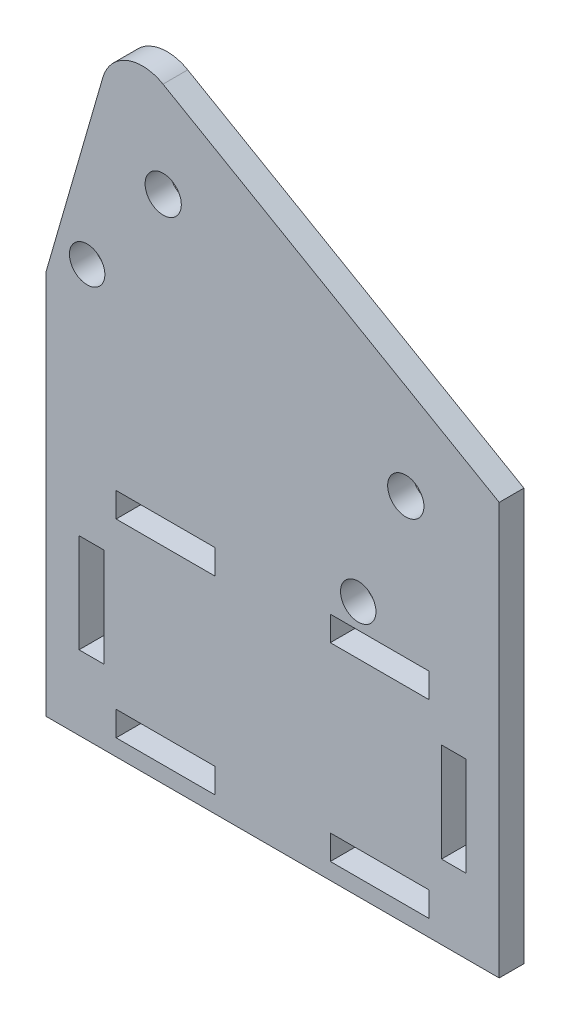
SolidWorks part; units mm, degrees
material "Thornel Mat VMA"
ref_plane "前视基准面" through (0, 0, 0) normal (0, 0, 1) x (1, 0, 0)
ref_plane "上视基准面" through (0, 0, 0) normal (0, 1, 0) x (1, 0, 0)
ref_plane "右视基准面" through (0, 0, 0) normal (1, 0, 0) x (0, 0, -1)
other "Configuration Table"
sketch "草图1" plane through (0, 0, 0) normal (0, 0, 1) x (1, 0, 0)
  line L0 (27.5, 15) -> (27.5, 35)
  line L1 (-27.5, 15) -> (27.5, 15)
  line L2 (-27.5, 15) -> (-27.5, -15)
  line L3 (-27.5, -15) -> (27.5, -15)
  line L4 (27.5, 15) -> (27.5, -15)
  line L5 (-27.5, 15) -> (27.5, -15) construction
  line L6 (-27.5, -15) -> (27.5, 15) construction
  line L7 (27.5, 35) -> (-27.5, 66.7543)
  line L8 (-27.5, 66.7543) -> (-27.5, 15)
  point P0 (0, 0)
  dimension "D1" = 30
  dimension "D2" = 55
  dimension "D3" = 20
  dimension "D4" = 60
extrude "凸台-拉伸1" add sketch "草图1" along normal blind 3 contours L7 L8 L1 L0 | L4 L1 L2 L3
sketch "草图2" plane through (0, 0, 3) normal (0, 0, 1) x (1, 0, 0)
  line L0 (0, 5.7338) -> (0, -5.8391) construction
  line L1 (-23.5, 13) -> (23.5, 13) construction
  line L2 (-23.5, 13) -> (-23.5, -13) construction
  line L3 (-23.5, -13) -> (23.5, -13) construction
  line L4 (23.5, 13) -> (23.5, -13) construction
  line L5 (-23.5, 13) -> (23.5, -13) construction
  line L6 (-23.5, -13) -> (23.5, 13) construction
  line L7 (-19, -13) -> (-7, -13)
  line L8 (-19, -13) -> (-19, -10)
  line L9 (-19, -10) -> (-7, -10)
  line L10 (-7, -13) -> (-7, -10)
  line L11 (19, -10) -> (7, -10)
  line L12 (7, -13) -> (7, -10)
  line L13 (19, -13) -> (7, -13)
  line L14 (19, -13) -> (19, -10)
  line L15 (-11.0901, 0) -> (13.8362, 0) construction
  line L16 (19, 13) -> (19, 10)
  line L17 (19, 13) -> (7, 13)
  line L18 (7, 13) -> (7, 10)
  line L19 (19, 10) -> (7, 10)
  line L20 (-19, 10) -> (-7, 10)
  line L21 (-7, 13) -> (-7, 10)
  line L22 (-19, 13) -> (-7, 13)
  line L23 (-19, 13) -> (-19, 10)
  line L24 (23.5, -6) -> (20.5, -6)
  line L25 (-23.5, 6) -> (-20.5, 6)
  line L26 (-23.5, 6) -> (-23.5, -6)
  line L27 (-23.5, -6) -> (-20.5, -6)
  line L28 (-20.5, 6) -> (-20.5, -6)
  line L29 (20.5, 6) -> (20.5, -6)
  line L30 (23.5, 6) -> (20.5, 6)
  line L31 (23.5, 6) -> (23.5, -6)
  point P0 (0, 0)
  point P30 (-20.5, 0)
  dimension "D1" = 47
  dimension "D2" = 26
  dimension "D3" = 3
  dimension "D4" = 12
  dimension "D5" = 7
  dimension "D6" = 3
  dimension "D7" = 12
extrude "切除-拉伸1" cut sketch "草图2" against normal blind 3
sketch "草图3" plane through (0, 0, 3) normal (0, 0, 1) x (1, 0, 0)
  line L0 (-13.2846, 47) -> (16.1603, 30) construction
  line L1 (27.5, 35) -> (-27.5, 66.7543) construction
  circle A0 centre (-13.2846, 47) radius 2.2
  circle A1 centre (16.1603, 30) radius 2.2
  dimension "D1" = 34
  dimension "D4" = 4.4
  dimension "D2" = 10
  dimension "D3" = 30
extrude "切除-拉伸2" cut sketch "草图3" against normal blind 10
sketch "草图4" plane through (0, 0, 3) normal (0, 0, 1) x (1, 0, 0)
  line L0 (-18.8397, 61.7543) -> (-27.5, 31.7543)
  line L1 (27.5, 35) -> (-27.5, 66.7543) construction
  line L2 (-27.5, 66.7543) -> (-27.5, -15) construction
  line L3 (-27.5, 31.7543) -> (-27.5, 66.7543)
  line L4 (-27.5, 66.7543) -> (-18.8397, 61.7543)
  point P6 (0, 0)
  dimension "D1" = 10
  dimension "D2" = 35
extrude "切除-拉伸3" cut sketch "草图4" against normal blind 10
fillet "圆角1" radius 5 1 edges at (-18.8397, 61.7543, 1.5)
sketch "草图5" plane through (0, 0, 0) normal (0, 0, -1) x (-1, 0, 0)
  circle A0 centre (-10.3923, 16.0096) radius 2.15
  circle A1 centre (22.5167, 35.0096) radius 2.15
  dimension "D1" = 4.3
extrude "切除-拉伸4" cut sketch "草图5" against normal blind 3
